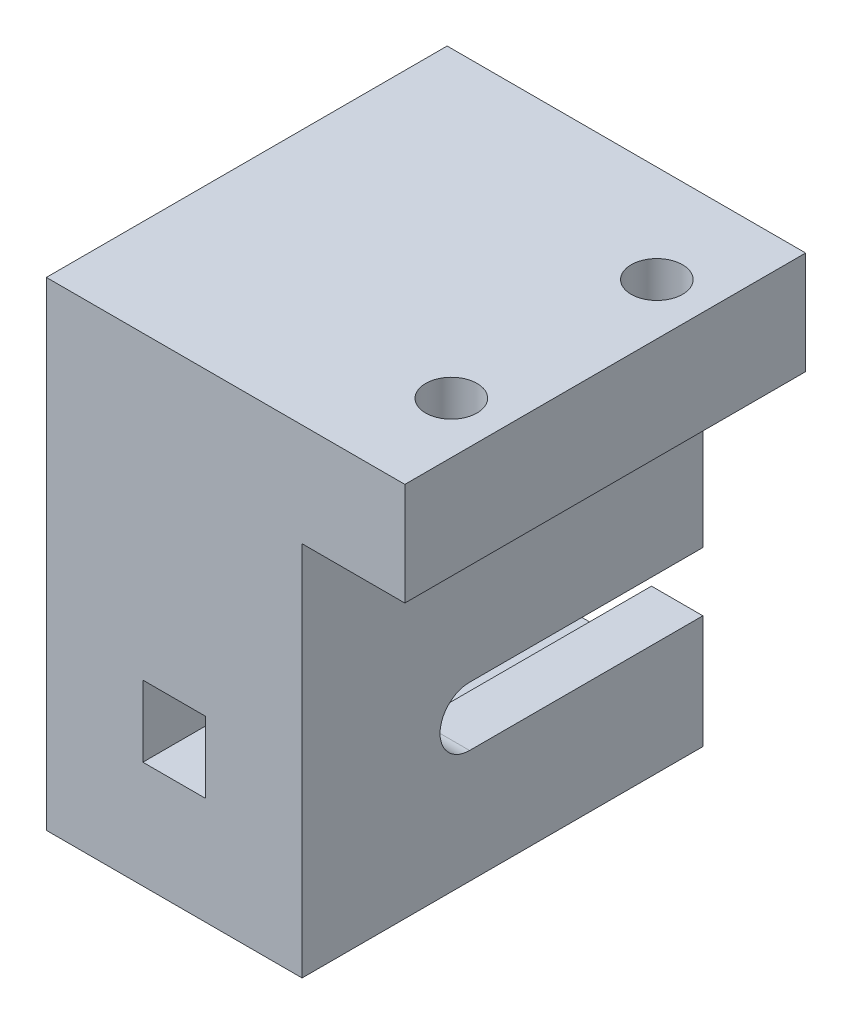
SolidWorks part; units mm, degrees
ref_plane "Front Plane" through (0, 0, 0) normal (0, 0, 1) x (1, 0, 0)
ref_plane "Top Plane" through (0, 0, 0) normal (0, 1, 0) x (1, 0, 0)
ref_plane "Right Plane" through (0, 0, 0) normal (1, 0, 0) x (0, 0, -1)
sketch "Sketch1" plane through (0, 0, 0) normal (0, 0, 1) x (1, 0, 0)
  line L0 (-15.8, 17.65) -> (15.8, 17.65)
  line L1 (-9.45, -11.3) -> (9.45, -11.3)
  line L2 (-9.45, -11.3) -> (-9.45, 11.3)
  line L3 (-9.45, 11.3) -> (9.45, 11.3)
  line L4 (9.45, -11.3) -> (9.45, 11.3)
  line L7 (15.8, -17.65) -> (15.8, 17.65)
  line L8 (-15.8, -17.65) -> (15.8, -17.65)
  line L9 (-15.8, -17.65) -> (-15.8, 17.65)
  point P0 (0, 0)
  dimension "D1" = 22.6
  dimension "D2" = 18.9
  dimension "D3" = 6.35
extrude "Boss-Extrude1" add sketch "Sketch1" along normal blind 40
sketch "Sketch2" plane through (0, 0, 40) normal (0, 0, 1) x (1, 0, 0)
  line L1 (-15.8, 17.65) -> (15.8, 17.65)
  line L2 (-15.8, 17.65) -> (-15.8, -17.65)
  line L3 (-15.8, -17.65) -> (15.8, -17.65)
  line L4 (15.8, 17.65) -> (15.8, -17.65)
  line L9 (-15.8, 17.65) -> (15.8, 17.65)
  line L10 (-15.8, 17.65) -> (-15.8, -17.65)
  line L11 (-15.8, -17.65) -> (15.8, -17.65)
  line L12 (15.8, 17.65) -> (15.8, -17.65)
  point P6 (0, 0)
  line M1 (-15.8, 17.65) -> (-15.8, -17.65)
  line M2 (-15.8, -17.65) -> (15.8, -17.65)
  line M3 (15.8, -17.65) -> (15.8, 17.65)
  line M4 (15.8, 17.65) -> (-15.8, 17.65)
  line M5 (9.45, 11.3) -> (9.45, -11.3)
  line M6 (9.45, -11.3) -> (-9.45, -11.3)
  line M7 (-9.45, -11.3) -> (-9.45, 11.3)
  line M8 (-9.45, 11.3) -> (9.45, 11.3)
extrude "Boss-Extrude2" add sketch "Sketch2" along normal blind 9.525 contours M4 M1 M2 M3 M8 M5 M6 M7 | M5 M8 M7 M6
sketch "Sketch3" plane through (0, 0, 40) normal (0, 0, -1) x (-1, 0, 0)
  line L1 (-3.8745, 4.3943) -> (3.8745, 4.3943)
  line L2 (-3.8745, 4.3943) -> (-3.8745, -4.3943)
  line L3 (-3.8745, -4.3943) -> (3.8745, -4.3943)
  line L4 (3.8745, 4.3943) -> (3.8745, -4.3943)
  line L5 (-3.8745, 4.3943) -> (3.8745, -4.3943) construction
  line L6 (-3.8745, -4.3943) -> (3.8745, 4.3943) construction
  point P0 (0, 0)
extrude "Cut-Extrude1" cut sketch "Sketch3" against normal blind 12.7
sketch "Sketch5" plane through (15.8, 0, 0) normal (1, 0, 0) x (0, 0, -1)
  line L1 (-40.0276, 0) -> (-28.8276, 0) construction
  line L2 (-28.8276, 3.65) -> (0, 3.65)
  line L3 (0, -17.65) -> (0, 17.65) construction
  line L4 (0, 3.65) -> (0, -3.65)
  line L5 (0, -3.65) -> (-28.8276, -3.65)
  arc A0 (-28.8276, 3.65) -> (-28.8276, -3.65) centre (-28.8276, 0) ccw
  dimension "D2" = 7.3
  dimension "D1" = 11.2
extrude "Cut-Extrude2" cut sketch "Sketch5" against normal blind 31.75
sketch "Sketch6" plane through (0, 17.65, 0) normal (0, 1, 0) x (1, 0, 0)
  line L1 (-15.8, 0) -> (15.8, 0)
  line L2 (-15.8, 0) -> (-15.8, -49.525)
  line L3 (-15.8, -49.525) -> (15.8, -49.525)
  line L4 (15.8, 0) -> (15.8, -49.525)
extrude "Boss-Extrude3" add sketch "Sketch6" along normal blind 11.176
sketch "Sketch7" plane through (15.8, 0, 0) normal (1, 0, 0) x (0, 0, -1)
  line L0 (0, 3.65) -> (0, 28.826) construction
  line L1 (-49.525, 28.826) -> (0, 28.826)
  line L2 (-49.525, 28.826) -> (-49.525, 22.476)
  line L3 (-49.525, 22.476) -> (0, 22.476)
  line L4 (0, 28.826) -> (0, 22.476)
  dimension "D1" = 6.35
extrude "Boss-Extrude4" add sketch "Sketch7" along normal blind 12.7 and the other way blind 44.45
sketch "Sketch8" plane through (0, 22.476, 0) normal (0, -1, 0) x (1, 0, 0)
  circle A1 centre (-22.225, 24.7625) radius 3.175
  circle A2 centre (22.15, 37.4346) radius 3.429
  circle A3 centre (22.15, 12.0346) radius 3.429
  dimension "D1" = 25.4
extrude "Cut-Extrude3" cut sketch "Sketch8" against normal blind 6.35
sketch "Sketch9" plane through (0, 22.476, 0) normal (0, -1, 0) x (1, 0, 0)
  line L1 (-15.8, 0) -> (-28.65, 0)
  line L2 (-15.8, 0) -> (-15.8, 49.525)
  line L3 (-15.8, 49.525) -> (-28.65, 49.525)
  line L4 (-28.65, 0) -> (-28.65, 49.525)
extrude "Cut-Extrude4" cut sketch "Sketch9" against normal blind 6.35
sketch "Sketch10" plane through (-15.8, 0, 0) normal (-1, 0, 0) x (0, 0, 1)
  circle A0 centre (28.8276, 0) radius 6.35
extrude "Cut-Extrude5" cut sketch "Sketch10" against normal blind 6.35
sketch "Sketch11" plane through (0, 28.826, 0) normal (0, 1, 0) x (1, 0, 0)
  line L1 (-15.8, 0) -> (28.5, 0)
  line L2 (-15.8, 0) -> (-15.8, -49.525)
  line L3 (-15.8, -49.525) -> (28.5, -49.525)
  line L4 (28.5, 0) -> (28.5, -49.525)
  circle A0 centre (22.15, -12.0346) radius 3.175
  circle A1 centre (22.15, -37.4346) radius 3.175
extrude "Boss-Extrude5" add sketch "Sketch11" along normal blind 12.7
sketch "Sketch12" plane through (0, 22.476, 0) normal (0, -1, 0) x (1, 0, 0)
  line L1 (15.8, 49.525) -> (28.5, 49.525)
  line L2 (15.8, 49.525) -> (15.8, 0)
  line L3 (15.8, 0) -> (28.5, 0)
  line L4 (28.5, 49.525) -> (28.5, 0)
  circle A0 centre (22.15, 37.4346) radius 3.175
  circle A1 centre (22.15, 12.0346) radius 3.175
extrude "Cut-Extrude6" cut sketch "Sketch12" against normal blind 6.35
